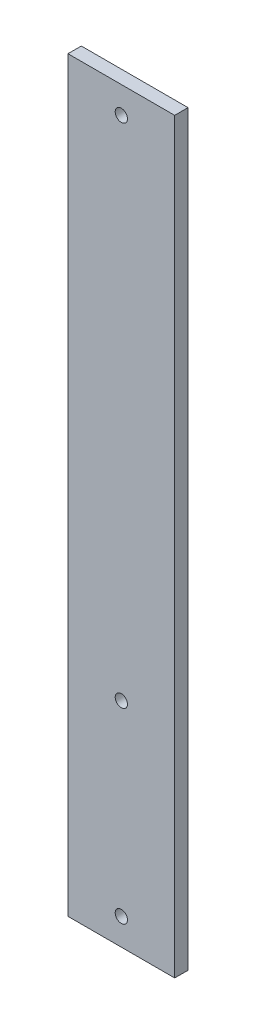
SolidWorks part; units mm, degrees
ref_plane "Front Plane" through (0, 0, 0) normal (0, 0, 1) x (1, 0, 0)
ref_plane "Top Plane" through (0, 0, 0) normal (0, 1, 0) x (1, 0, 0)
ref_plane "Right Plane" through (0, 0, 0) normal (1, 0, 0) x (0, 0, -1)
sketch "Sketch2" plane through (0, 0, 0) normal (0, 0, 1) x (1, 0, 0)
  line L0 (12.7, 177.8) -> (12.7, 0) construction
  line L1 (0, 0) -> (25.4, 0)
  line L2 (0, 0) -> (0, 177.8)
  line L3 (0, 177.8) -> (25.4, 177.8)
  line L4 (25.4, 0) -> (25.4, 177.8)
  circle A0 centre (12.7, 171.45) radius 1.4605
  circle A1 centre (12.7, 50.8) radius 1.4605
  circle A2 centre (12.7, 6.35) radius 1.4605
  dimension "D3" = 2.921
  dimension "D5" = 2.921
  dimension "D7" = 2.921
  dimension "D1" = 25.4
  dimension "D2" = 177.8
  dimension "D4" = 6.35
  dimension "D6" = 120.65
  dimension "D8" = 6.35
extrude "Boss-Extrude1" add sketch "Sketch2" along normal blind 3.175
